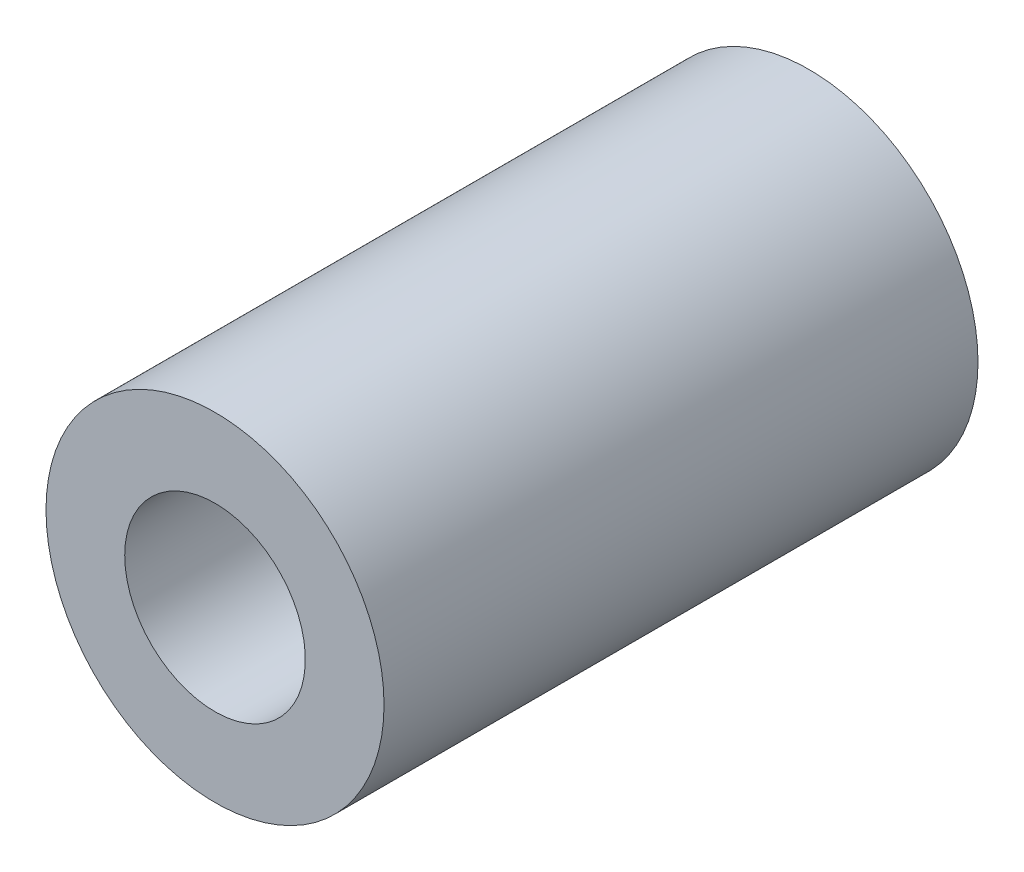
SolidWorks part; units mm, degrees
ref_plane "Front Plane" through (0, 0, 0) normal (0, 0, 1) x (1, 0, 0)
ref_plane "Top Plane" through (0, 0, 0) normal (0, 1, 0) x (1, 0, 0)
ref_plane "Right Plane" through (0, 0, 0) normal (1, 0, 0) x (0, 0, -1)
sketch "Sketch1" plane through (0, 0, 0) normal (0, 0, 1) x (1, 0, 0)
  circle A0 centre (0, 0) radius 4.75
  circle A1 centre (0, 0) radius 8.89
  dimension "D1" = 9.5
  dimension "D2" = 17.78
extrude "Boss-Extrude1" add sketch "Sketch1" along normal blind 31.242 contours A0
